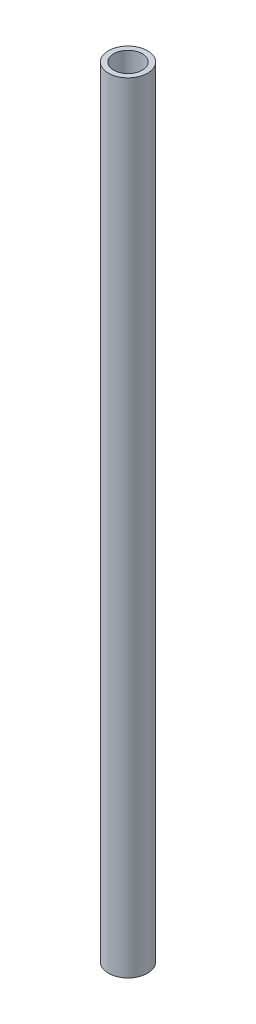
SolidWorks part; units mm, degrees
material "AISI 316 Stainless Steel Sheet (SS)"
ref_plane "Front Plane" through (0, 0, 0) normal (0, 0, 1) x (1, 0, 0)
ref_plane "Top Plane" through (0, 0, 0) normal (0, 1, 0) x (1, 0, 0)
ref_plane "Right Plane" through (0, 0, 0) normal (1, 0, 0) x (0, 0, -1)
sketch "Sketch1" plane through (0, 0, 0) normal (0, 1, 0) x (1, 0, 0)
  circle A0 centre (0, 0) radius 0.4508
  circle A1 centre (0, 0) radius 0.3302
  dimension "D1" = 0.6604
  dimension "D2" = 0.9017
extrude "Boss-Extrude1" add sketch "Sketch1" along normal blind 18 contours A0 A1
